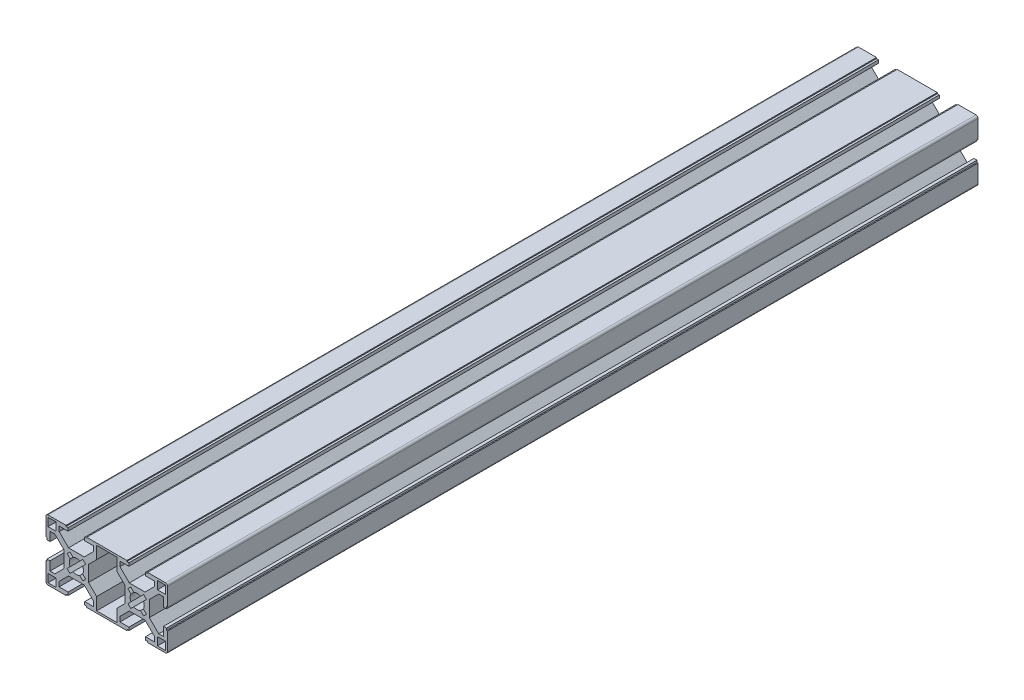
SolidWorks part; units mm, degrees
material "6063-O"
ref_plane "Plano frontal" through (0, 0, 0) normal (0, 0, 1) x (1, 0, 0)
ref_plane "Plano superior" through (0, 0, 0) normal (0, 1, 0) x (1, 0, 0)
ref_plane "Plano direito" through (0, 0, 0) normal (1, 0, 0) x (0, 0, -1)
sketch "Esboço1" plane through (0, 0, 0) normal (0, 0, 1) x (1, 0, 0)
  line L5 (0, 0) -> (-17.7944, 17.7944) construction
  line L6 (0, 3.5) -> (0, 6)
  line L8 (0, 6) -> (-3.8787, 6)
  line L9 (-3.5, 0) -> (-6, 0)
  line L48 (-6, 0) -> (-6, 3.8787)
  line L49 (-3.8787, 6) -> (-8.5, 10.6213)
  line L50 (-6, 3.8787) -> (-10.6213, 8.5)
  line L51 (0, 0) -> (-12.921, 0) construction
  line L52 (-8.5, 13) -> (-4.1, 13)
  line L53 (-4.1, 13) -> (-4.1, 14.5)
  line L54 (-4.1, 14.5) -> (-5.1, 14.5)
  line L55 (-5.1, 14.5) -> (-5.1, 15)
  line L56 (-5.1, 15) -> (-15, 15)
  line L57 (-15, 5.1) -> (-15, 15)
  line L58 (-14.5, 5.1) -> (-15, 5.1)
  line L59 (-14.5, 4.1) -> (-14.5, 5.1)
  line L60 (-13, 4.1) -> (-14.5, 4.1)
  line L61 (-13, 8.5) -> (-13, 4.1)
  line L62 (-1.6646, 3.0788) -> (-3.182, 4.5962)
  line L63 (-3.0788, 1.6646) -> (-4.5962, 3.182)
  line L64 (-4.5962, 3.182) -> (-3.182, 4.5962)
  line L65 (-8.5, 13) -> (-8.5, 10.6213)
  line L66 (-10, 14) -> (-14, 14)
  line L67 (-10, 14) -> (-10, 10)
  line L68 (-10, 10) -> (-14, 10)
  line L69 (-14, 14) -> (-14, 10)
  line L70 (-10, 14) -> (-14, 10) construction
  line L71 (-10, 10) -> (-14, 14) construction
  line L72 (-13, 8.5) -> (-10.6213, 8.5)
  circle A1 centre (0, 0) radius 3.5
  point P25 (-12, 12)
  dimension "D5" = 10.9
  dimension "D9" = 5.5
  dimension "D10" = 2
  dimension "D11" = 4
  dimension "D12" = 4
  dimension "D13" = 1
  dimension "D1" = 7
  dimension "D2" = 6
  dimension "D3" = 3
  dimension "D4" = 9.9
  dimension "D6" = 0.5
  dimension "D7" = 1.5
  dimension "D8" = 15
  dimension "D14" = 6.5
extrude "Ressalto-extrusão1" add sketch "Esboço1" along normal blind 400 contours A1 L6 L8 L49 L65 L52 L53 L54 L55 L56 L57 L58 L59 L60 L61 L72 L50 L48 L9 L63 L64 L62 L69 L66 L67 L68
sketch "Esboço3" plane through (0, 0, 0) normal (1, 0, 0) x (0, 0, -1)
  line L0 (0, 0) -> (-1000, 0) construction
  dimension "D1" = 1000
pattern_circular "PadrãoCircular1" count 4 every 90 about axis through (0, 0, 0) along (0, 0, 1) of "Ressalto-extrusão1"
pattern_linear "Padrão linear1" count 2 spacing 30 along (1, 0, 0) of "Ressalto-extrusão1", "PadrãoCircular1"
sketch "Esboço4" plane through (0, 0, 0) normal (0, 0, -1) x (-1, 0, 0)
  line L0 (-20, 14) -> (-20, -14)
  line L1 (-20, -14) -> (-10, -14)
  line L2 (-10, -14) -> (-10, 14)
  line L3 (-10, 14) -> (-20, 14)
extrude "Corte-extrusão1" cut sketch "Esboço4" against normal through all
fillet "Filete1" radius 1 4 edges at (45, -15, 200) (45, 15, 200) (-15, 15, 200) (-15, -15, 200)
ref_plane "Plane1" through (0, 0, 200) normal (0, 0, -1) x (-1, 0, 0)
ref_plane "Plane2" through (15, 0, 0) normal (-1, 0, 0) x (0, 0, 1)
